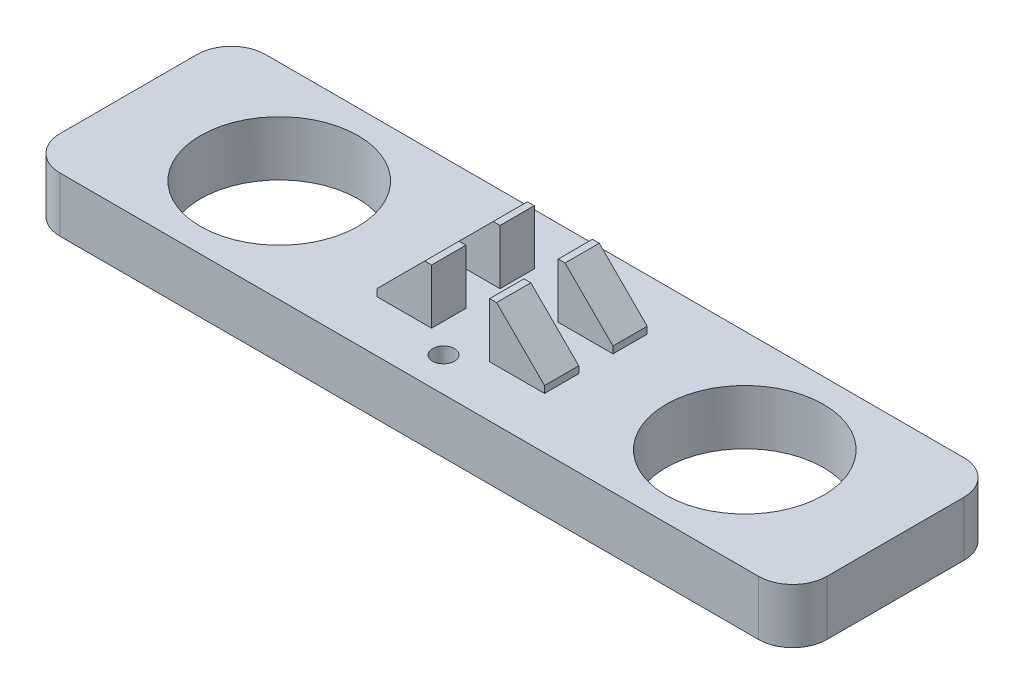
SolidWorks part; units mm, degrees
ref_plane "Front Plane" through (0, 0, 0) normal (0, 0, 1) x (1, 0, 0)
ref_plane "Top Plane" through (0, 0, 0) normal (0, 1, 0) x (1, 0, 0)
ref_plane "Right Plane" through (0, 0, 0) normal (1, 0, 0) x (0, 0, -1)
sketch "Sketch1" plane through (0, 0, 0) normal (0, 1, 0) x (1, 0, 0)
  line L1 (0, 0) -> (60, 0)
  line L2 (0, 0) -> (0, 30)
  line L3 (0, 30) -> (60, 30)
  line L4 (60, 0) -> (60, 30)
  circle A0 centre (22, 15) radius 11.5
  point P7 (0, 15)
  dimension "D3" = 23
  dimension "D4" = 22
  dimension "D1" = 60
  dimension "D2" = 30
extrude "Boss-Extrude1" add sketch "Sketch1" along normal blind 5
sketch "Sketch2" plane through (0, 5, 0) normal (0, 1, 0) x (1, 0, 0)
  line L0 (60, 0) -> (60, 30) construction
  line L1 (0, 0) -> (60, 0) construction
  line L2 (60, 30) -> (0, 30) construction
  circle A0 centre (56, 25) radius 1.6
  circle A1 centre (56, 5) radius 1.6
  dimension "D1" = 3.2
  dimension "D4" = 5
  dimension "D2" = 4
  dimension "D3" = 5
extrude "Cut-Extrude1" cut sketch "Sketch2" against normal through all
fillet "Fillet1" radius 5 2 edges at (0, 2.5, 0) (0, 2.5, -30)
sketch "Sketch6" plane through (0, 0, 0) normal (0, -1, 0) x (1, 0, 0)
  line L12 (60, 0) -> (5, 0)
  line L13 (0, -5) -> (0, -25)
  line L14 (5, -30) -> (60, -30)
  line L15 (60, -30) -> (60, 0)
  line L18 (60, 0) -> (5, 0)
  line L19 (0, -5) -> (0, -25)
  line L20 (5, -30) -> (60, -30)
  line L21 (60, -30) -> (60, 0)
  arc A8 (5, 0) -> (0, -5) centre (5, -5) ccw
  arc A9 (0, -25) -> (5, -30) centre (5, -25) ccw
  arc A12 (5, 0) -> (0, -5) centre (5, -5) ccw
  arc A13 (0, -25) -> (5, -30) centre (5, -25) ccw
  dimension "D1" = 0
extrude "Boss-Extrude4" add sketch "Sketch6" along normal blind 3
ref_plane "Plane1" through (56, 0, 0) normal (1, 0, 0) x (0, 0, -1)
mirror "Mirror1" about plane through (56, 0, 0) normal (1, 0, 0) of "Boss-Extrude4", "Fillet1", "Cut-Extrude1", "Boss-Extrude1"
sketch "Sketch7" plane through (0, 5, 0) normal (0, 1, 0) x (1, 0, 0)
  line L0 (0, 25) -> (0, 5) construction
  line L1 (43.75, 22.5) -> (51.75, 22.5)
  line L2 (43.75, 22.5) -> (43.75, 17.5)
  line L3 (43.75, 17.5) -> (51.75, 17.5)
  line L4 (51.75, 22.5) -> (51.75, 17.5)
  line L5 (60.25, 22.5) -> (68.25, 22.5)
  line L6 (60.25, 22.5) -> (60.25, 17.5)
  line L7 (60.25, 17.5) -> (68.25, 17.5)
  line L8 (68.25, 22.5) -> (68.25, 17.5)
  line L9 (5, 0) -> (107, 0) construction
  line L10 (107, 30) -> (5, 30) construction
  point P8 (0, 15)
  point P9 (51.75, 20)
  point P12 (56, 0)
  point P13 (43.75, 20)
  point P16 (0, 0)
  point P17 (0, 0)
  point P18 (0, 0)
  dimension "D1" = 8.5
  dimension "D2" = 5
  dimension "D3" = 8
  dimension "D4" = 4.25
  dimension "D5" = 7.5
extrude "Boss-Extrude5" add sketch "Sketch7" along normal blind 8
chamfer "Chamfer1" distance 7 angle 45 2 edges at (68.25, 13, -20) (43.75, 13, -20)
ref_plane "Plane2" through (0, 0, -15) normal (0, 0, -1) x (-1, 0, 0)
mirror "Mirror2" about plane through (0, 0, -15) normal (0, 0, -1) of "Chamfer1", "Boss-Extrude5"
